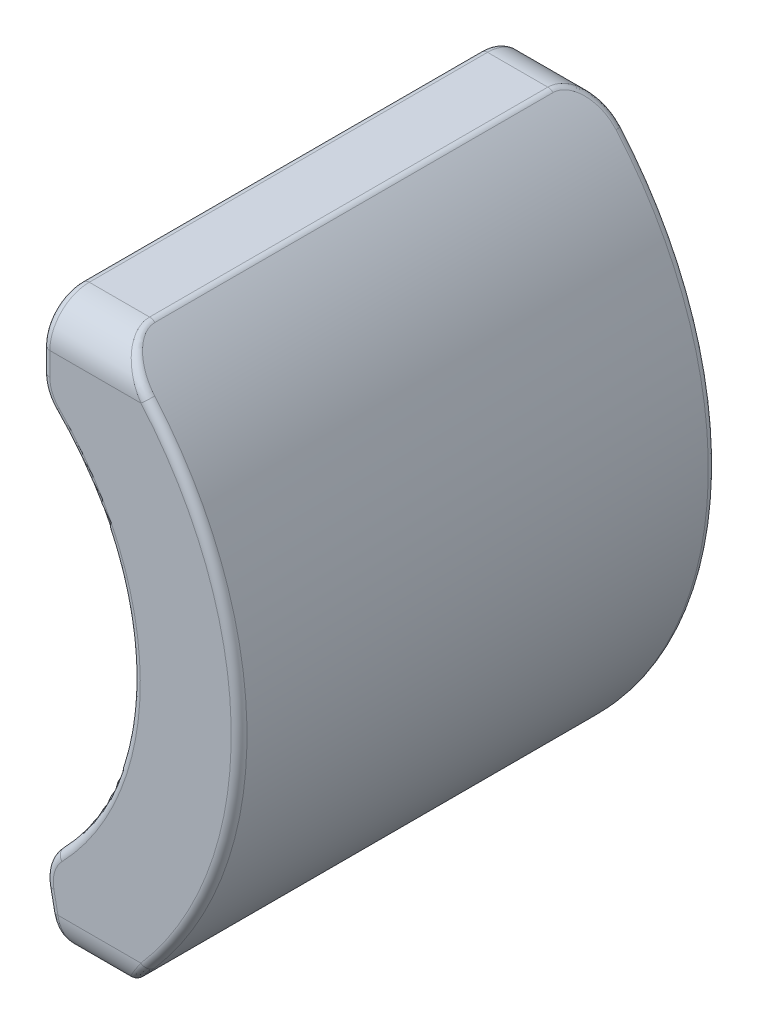
SolidWorks part; units mm, degrees
other "magnete 1"
material "Gray Cast Iron"
ref_plane "Front Plane" through (0, 0, 0) normal (0, 0, 1) x (1, 0, 0)
ref_plane "Top Plane" through (0, 0, 0) normal (0, 1, 0) x (1, 0, 0)
ref_plane "Right Plane" through (0, 0, 0) normal (1, 0, 0) x (0, 0, -1)
sketch "Sketch1" plane through (0, 0, 0) normal (0, 0, 1) x (1, 0, 0)
  line L0 (-3.2786, 3.775) -> (3.2786, 3.775) construction
  line L1 (-5, 3.775) -> (5, 3.775) construction
  line L2 (-5, 3.775) -> (-5, -3.775) construction
  line L3 (-5, -3.775) -> (5, -3.775) construction
  line L4 (5, 3.775) -> (5, -3.775) construction
  line L5 (-5, 3.775) -> (5, -3.775) construction
  line L6 (-5, -3.775) -> (5, 3.775) construction
  line L7 (3.2786, -3.775) -> (-3.2786, -3.775) construction
  line L8 (2.3, -2.5671) -> (2.3, -3.575) construction
  line L9 (2.3, -3.575) -> (2.5, -3.575) construction
  line L10 (0, 0) -> (0, 3.575) construction
  line L11 (2.5, -3.575) -> (3.203, -3.575)
  line L12 (3.203, 3.575) -> (2.3, 3.575)
  line L14 (2.3, 3.575) -> (2.3, 2.5671)
  line L16 (3.203, -3.575) -> (-3.203, -3.575) construction
  line L17 (-3.203, 3.575) -> (3.203, 3.575) construction
  line L18 (2.5, -3.575) -> (2.3, -2.5671)
  arc A0 (-3.2786, 3.775) -> (-3.2786, -3.775) centre (0, 0) ccw construction
  arc A1 (3.2786, 3.775) -> (3.2786, -3.775) centre (0, 0) cw construction
  arc A2 (-3.203, 3.575) -> (-3.203, -3.575) centre (0, 0) ccw construction
  arc A3 (3.203, 3.575) -> (3.203, -3.575) centre (0, 0) cw
  arc A4 (2.3, 2.5671) -> (2.3, -2.5671) centre (0, 0) cw
  point P0 (0, 0)
  dimension "D3" = 5
  dimension "D1" = 7.55
  dimension "D2" = 10
  dimension "D4" = 0.2
  dimension "D5" = 2.7
  dimension "D6" = 0.2
extrude "Boss-Extrude1" add sketch "Sketch1" along normal up to surface (6.05 mm away)
fillet "Fillet1" radius 0.5 6 edges at (2.3, -2.5671, 3.025) (2.8515, -3.575, 0) (2.8515, -3.575, 6.05) (2.7515, 3.575, 0) (2.7515, 3.575, 6.05) (2.3, 2.5671, 3.025)
fillet "Fillet2" radius 0.1 24 edges at (3.339, -3.4484, 5.8825) (3.203, -3.575, 3.025) (3.2701, -3.5137, 0.2602) (4.8, 0, 0) (3.4466, 0.0272, 0) (2.3637, -2.5964, 0) (2.3769, -2.9547, 0) (2.4709, -3.4286, 0.1464) (2.5, -3.575, 3.025) (2.4709, -3.4286, 5.9036) (2.3637, -2.5964, 6.05) (3.4466, 0.0272, 6.05) (4.8, 0, 6.05) (2.3769, -2.9547, 6.05) (3.339, 3.4484, 0.1675) (3.203, 3.575, 3.025) (3.2701, 3.5137, 5.7898) (2.3, 3.4286, 5.9036) (2.3, 3.575, 3.025) (2.3, 3.4286, 0.1464) (2.3, 2.9283, 0) (2.3377, 2.5909, 0) (2.3377, 2.5909, 6.05) (2.3, 2.9283, 6.05)
